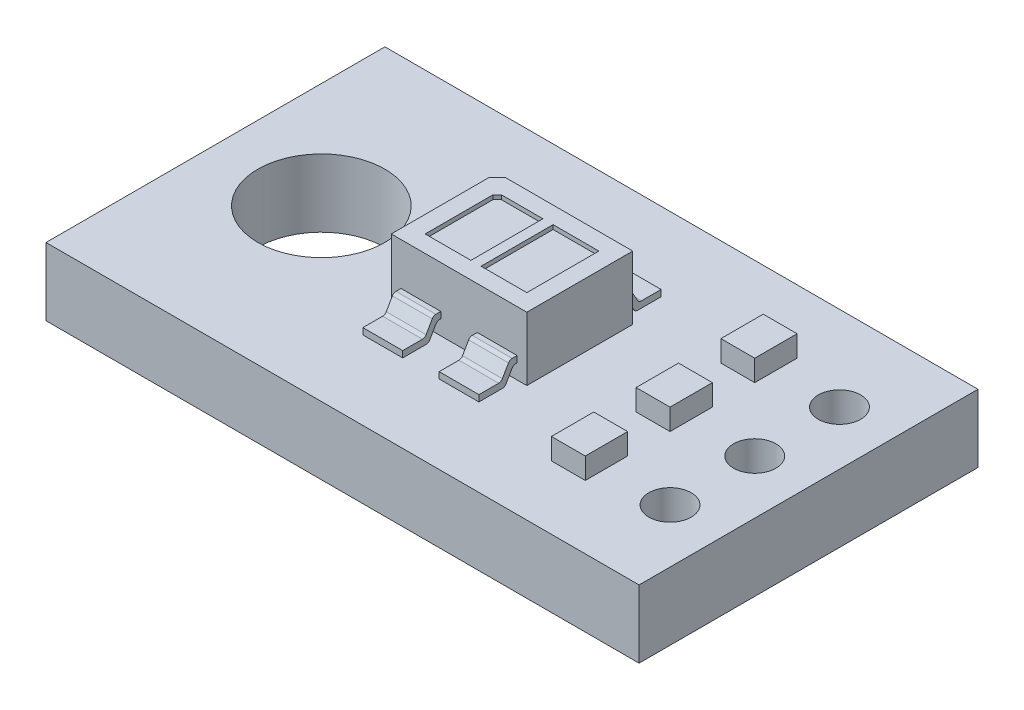
SolidWorks part; units mm, degrees
ref_plane "Front Plane" through (0, 0, 0) normal (0, 0, 1) x (1, 0, 0)
ref_plane "Top Plane" through (0, 0, 0) normal (0, 1, 0) x (1, 0, 0)
ref_plane "Right Plane" through (0, 0, 0) normal (1, 0, 0) x (0, 0, -1)
sketch "Sketch1" plane through (0, 0, 0) normal (0, 1, 0) x (1, 0, 0)
  line L0 (5.73, 4) -> (5.73, -4) construction
  line L1 (7, 4) -> (-7, 4)
  line L2 (7, 4) -> (7, -4)
  line L3 (7, -4) -> (-7, -4)
  line L4 (-7, 4) -> (-7, -4)
  line L5 (7, 4) -> (-7, -4) construction
  line L6 (7, -4) -> (-7, 4) construction
  circle A0 centre (5.73, 0) radius 0.5
  circle A1 centre (5.73, -2) radius 0.5
  circle A2 centre (5.73, 2) radius 0.5
  circle A3 centre (-4.5, 0) radius 1.5
  point P0 (0, 0)
  point P8 (5.73, 2)
  point P9 (5.73, 0)
  point P10 (5.73, -2)
  dimension "D4" = 1
  dimension "D5" = 3
  dimension "D1" = 14
  dimension "D2" = 8
  dimension "D3" = 1.27
  dimension "D6" = 2.5
extrude "Boss-Extrude1" add sketch "Sketch1" along normal blind 1.6 contours L1 L4 L3 L2 A3 A2 A1 A0
sketch "Sketch2" plane through (0, 1.6, 0) normal (0, 1, 0) x (1, 0, 0)
  line L0 (3.83, 4) -> (3.83, -4) construction
  line L1 (4.23, 2.5) -> (3.43, 2.5)
  line L2 (4.23, 2.5) -> (4.23, 1.5)
  line L3 (4.23, 1.5) -> (3.43, 1.5)
  line L4 (3.43, 2.5) -> (3.43, 1.5)
  line L5 (4.23, 2.5) -> (3.43, 1.5) construction
  line L6 (4.23, 1.5) -> (3.43, 2.5) construction
  line L7 (7, 4) -> (-7, 4) construction
  line L8 (7, -4) -> (-7, -4) construction
  line L10 (4.23, 0.5) -> (3.43, 0.5)
  line L11 (4.23, 0.5) -> (4.23, -0.5)
  line L12 (4.23, -0.5) -> (3.43, -0.5)
  line L13 (3.43, 0.5) -> (3.43, -0.5)
  line L14 (4.23, 0.5) -> (3.43, -0.5) construction
  line L15 (4.23, -0.5) -> (3.43, 0.5) construction
  line L16 (4.23, -1.5) -> (3.43, -1.5)
  line L17 (4.23, -1.5) -> (4.23, -2.5)
  line L18 (4.23, -2.5) -> (3.43, -2.5)
  line L19 (3.43, -1.5) -> (3.43, -2.5)
  line L20 (4.23, -1.5) -> (3.43, -2.5) construction
  line L21 (4.23, -2.5) -> (3.43, -1.5) construction
  circle A0 centre (5.73, 2) radius 0.5 construction
  point P0 (3.83, 2)
  point P13 (3.83, 2)
  point P14 (3.83, 0)
  point P15 (3.83, -2)
  point P16 (3.83, -2)
  point P17 (3.83, 0)
  dimension "D3" = 1.5
  dimension "D1" = 0.8
  dimension "D2" = 1
extrude "Boss-Extrude2" add sketch "Sketch2" along normal blind 0.5 separate body
sketch "Sketch3" plane through (0, 1.6, 0) normal (0, 1, 0) x (1, 0, 0)
  line L0 (1.6, 1.25) -> (-1.4, 1.25)
  line L2 (-1.6, 1.05) -> (-1.6, -1.25)
  line L3 (-1.6, -1.25) -> (1.6, -1.25)
  line L4 (1.6, -1.25) -> (1.6, 1.25)
  line L5 (-1.4, 1.25) -> (-1.6, 1.05)
  point P1 (-1.6, 1.25)
  point P3 (1.6, 0)
  point P6 (0, -1.25)
  dimension "D1" = 3.2
  dimension "D2" = 2.5
extrude "Boss-Extrude3" add sketch "Sketch3" along normal blind 1.5 separate body
sketch "Sketch4" plane through (0, 3.1, 0) normal (0, 1, 0) x (1, 0, 0)
  line L0 (0.66, 0) -> (0, 0) construction
  line L1 (1.2, 0.85) -> (0.12, 0.85)
  line L2 (1.2, 0.85) -> (1.2, -0.85)
  line L3 (1.2, -0.85) -> (0.12, -0.85)
  line L4 (0.12, 0.85) -> (0.12, -0.85)
  line L5 (1.2, 0.85) -> (0.12, -0.85) construction
  line L6 (1.2, -0.85) -> (0.12, 0.85) construction
  line L7 (-0.12, 0.85) -> (-1.1, 0.85)
  line L8 (-0.12, 0.85) -> (-0.12, -0.85)
  line L9 (-0.12, -0.85) -> (-1.2, -0.85)
  line L10 (-1.2, 0.75) -> (-1.2, -0.85)
  line L11 (-0.12, 0.85) -> (-1.2, -0.85) construction
  line L12 (-0.12, -0.85) -> (-1.2, 0.85) construction
  line L13 (0, 0) -> (-0.66, 0) construction
  line L15 (-1.6, 1.05) -> (-1.6, -1.25) construction
  line L16 (-1.6, -1.25) -> (1.6, -1.25) construction
  line L17 (-1.1, 0.85) -> (-1.2, 0.75)
  point P0 (0.66, 0)
  point P5 (-0.66, 0)
  dimension "D1" = 1.32
  dimension "D2" = 0.4
  dimension "D3" = 0.4
extrude "Cut-Extrude1" cut sketch "Sketch4" against normal blind 0.1
sketch "Sketch5" plane through (-1.6, 0, 0) normal (-1, 0, 0) x (0, 0, 1)
  line L0 (1.25, 2.1) -> (1.3668, 2.1)
  line L1 (1.25, 3.1) -> (1.25, 1.6) construction
  line L2 (1.4534, 2.05) -> (1.5977, 1.8)
  line L3 (1.6843, 1.75) -> (2.15, 1.75)
  line L4 (2.15, 1.75) -> (2.15, 1.6)
  line L5 (-4, 1.6) -> (4, 1.6) construction
  line L6 (2.15, 1.6) -> (1.5977, 1.6)
  line L7 (1.5111, 1.65) -> (1.3668, 1.9)
  line L8 (1.2802, 1.95) -> (1.25, 1.95)
  line L9 (-1.25, 2.35) -> (1.25, 2.35) construction
  line L10 (-1.25, 3.1) -> (-1.25, 1.6) construction
  line L11 (0, 2.35) -> (0, 1.6) construction
  line L12 (-1.25, 2.1) -> (-1.25, 1.95)
  line L13 (-1.2802, 1.95) -> (-1.25, 1.95)
  line L14 (-1.5111, 1.65) -> (-1.3668, 1.9)
  line L15 (-2.15, 1.6) -> (-1.5977, 1.6)
  line L16 (-2.15, 1.75) -> (-2.15, 1.6)
  line L17 (-1.6843, 1.75) -> (-2.15, 1.75)
  line L18 (-1.4534, 2.05) -> (-1.5977, 1.8)
  line L19 (1.25, 2.1) -> (1.25, 1.95)
  line L20 (-1.25, 2.1) -> (-1.3668, 2.1)
  arc A0 (1.5977, 1.8) -> (1.6843, 1.75) centre (1.6843, 1.85) ccw
  arc A1 (1.5977, 1.6) -> (1.5111, 1.65) centre (1.5977, 1.7) cw
  arc A2 (1.3668, 1.9) -> (1.2802, 1.95) centre (1.2802, 1.85) ccw
  arc A3 (1.3668, 2.1) -> (1.4534, 2.05) centre (1.3668, 2) cw
  arc A4 (-1.3668, 2.1) -> (-1.4534, 2.05) centre (-1.3668, 2) ccw
  arc A5 (-1.3668, 1.9) -> (-1.2802, 1.95) centre (-1.2802, 1.85) cw
  arc A6 (-1.5977, 1.6) -> (-1.5111, 1.65) centre (-1.5977, 1.7) ccw
  arc A7 (-1.5977, 1.8) -> (-1.6843, 1.75) centre (-1.6843, 1.85) cw
  point P18 (1.54, 1.6)
  point P43 (-1.54, 1.6)
  dimension "D8" = 0.1
  dimension "D1" = 120
  dimension "D2" = 0.9
  dimension "D3" = 0.61
  dimension "D4" = 0.5
  dimension "D5" = 0.15
  dimension "D6" = 0.15
  dimension "D7" = 0.15
extrude "Boss-Extrude4" add sketch "Sketch5" against normal up to surface (3.2 mm away) separate body up to face at (1.6, 2.35, 0)
sketch "Sketch6" plane through (0, 3.1, 0) normal (0, 1, 0) x (1, 0, 0)
  line L0 (1.6, 1.25) -> (-1.4, 1.25) construction
  line L1 (1.6, 2.15) -> (1.37, 2.15)
  line L2 (1.6, 2.15) -> (1.6, 1.25)
  line L3 (1.6, 1.25) -> (1.37, 1.25)
  line L4 (1.37, 2.15) -> (1.37, 1.25)
  line L5 (1.6, 2.15) -> (-1.6, 2.15) construction
  line L6 (0.43, 2.15) -> (-0.43, 2.15)
  line L7 (0.43, 2.15) -> (0.43, 1.25)
  line L8 (0.43, 1.25) -> (-0.43, 1.25)
  line L9 (-0.43, 2.15) -> (-0.43, 1.25)
  line L10 (1.6, 0) -> (-1.6, 0) construction
  line L11 (-1.37, 2.15) -> (-1.6, 2.15)
  line L12 (-1.37, 2.15) -> (-1.37, 1.25)
  line L13 (-1.37, 1.25) -> (-1.6, 1.25)
  line L14 (-1.6, 2.15) -> (-1.6, 1.25)
  line L15 (1.6, -1.25) -> (1.6, 1.25) construction
  line L16 (-1.6, 1.05) -> (-1.6, -1.25) construction
  line L17 (-1.6, -2.15) -> (-1.6, -1.25)
  line L18 (-1.37, -1.25) -> (-1.6, -1.25)
  line L19 (-1.37, -2.15) -> (-1.37, -1.25)
  line L20 (-1.37, -2.15) -> (-1.6, -2.15)
  line L21 (-0.43, -2.15) -> (-0.43, -1.25)
  line L22 (0.43, -1.25) -> (-0.43, -1.25)
  line L23 (0.43, -2.15) -> (0.43, -1.25)
  line L24 (0.43, -2.15) -> (-0.43, -2.15)
  line L25 (1.37, -2.15) -> (1.37, -1.25)
  line L26 (1.6, -1.25) -> (1.37, -1.25)
  line L27 (1.6, -2.15) -> (1.6, -1.25)
  line L28 (1.6, -2.15) -> (1.37, -2.15)
  dimension "D2" = 0.86
  dimension "D1" = 0.94
  dimension "D3" = 0.94
extrude "Cut-Extrude2" cut sketch "Sketch6" against normal up to surface (1.5 mm away) contours L12 L11 L14 L13 | L7 L6 L9 L8 | L2 L1 L4 L3 | L25 L26 L27 L28 | L21 L22 L23 L24 | L17 L18 L19 L20
equation "\"D3@Sketch6\"=\"D1@Sketch6\""
